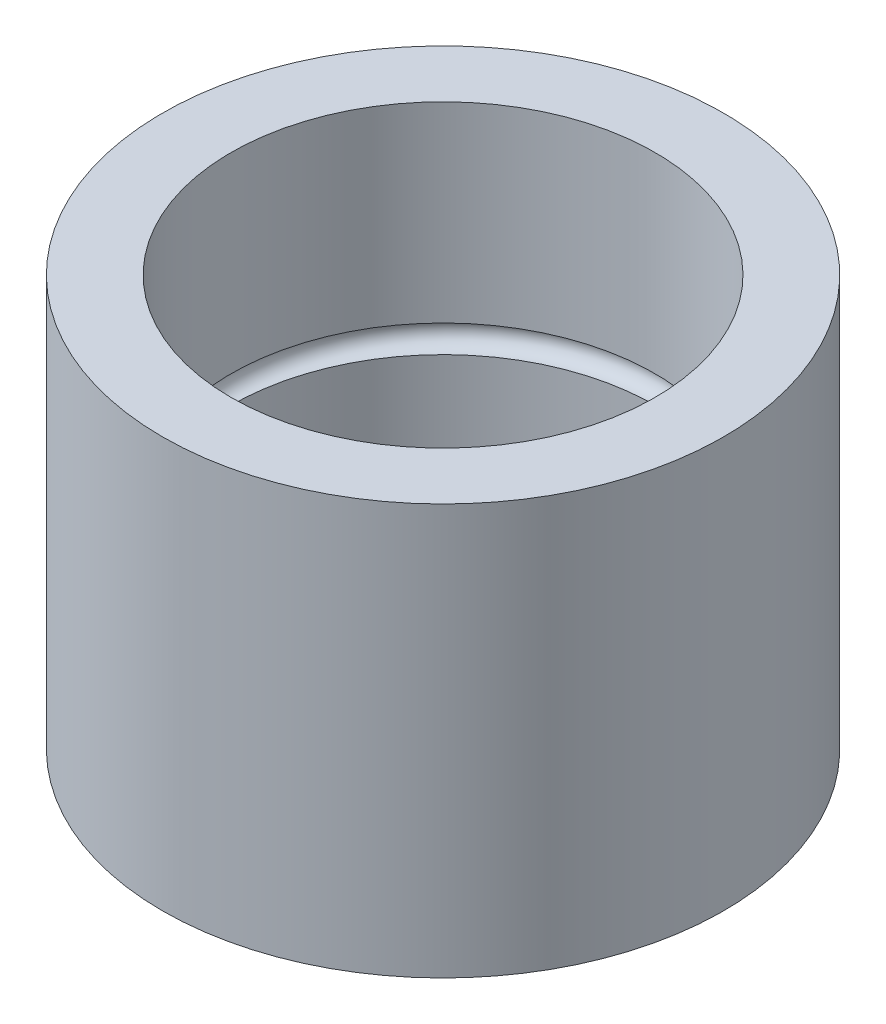
SolidWorks part; units mm, degrees
material "Bronze comercial , UNS C22000 (Bronze 90-10)"
ref_plane "Plano frontal" through (0, 0, 0) normal (0, 0, 1) x (1, 0, 0)
ref_plane "Plano superior" through (0, 0, 0) normal (0, 1, 0) x (1, 0, 0)
ref_plane "Plano direito" through (0, 0, 0) normal (1, 0, 0) x (0, 0, -1)
sketch "Esboço1" plane through (0, 0, 0) normal (0, 0, 1) x (1, 0, 0)
  line L0 (0, 15) -> (0, -15) construction
  line L1 (-15.5, -1) -> (-15.5, -15)
  line L2 (-15.5, 15) -> (-20.5, 15)
  line L3 (-15.5, 15) -> (-15.5, 1)
  line L4 (-15.5, -15) -> (-20.5, -15)
  line L5 (-20.5, 15) -> (-20.5, -15)
  arc A0 (-15.5, 1) -> (-15.5, -1) centre (-15.5, 0) ccw
  point P10 (0, 0)
  dimension "D4" = 2
  dimension "D1" = 41
  dimension "D2" = 31
  dimension "D3" = 30
revolve "Revolução1" add sketch "Esboço1" angle 360 about L0
